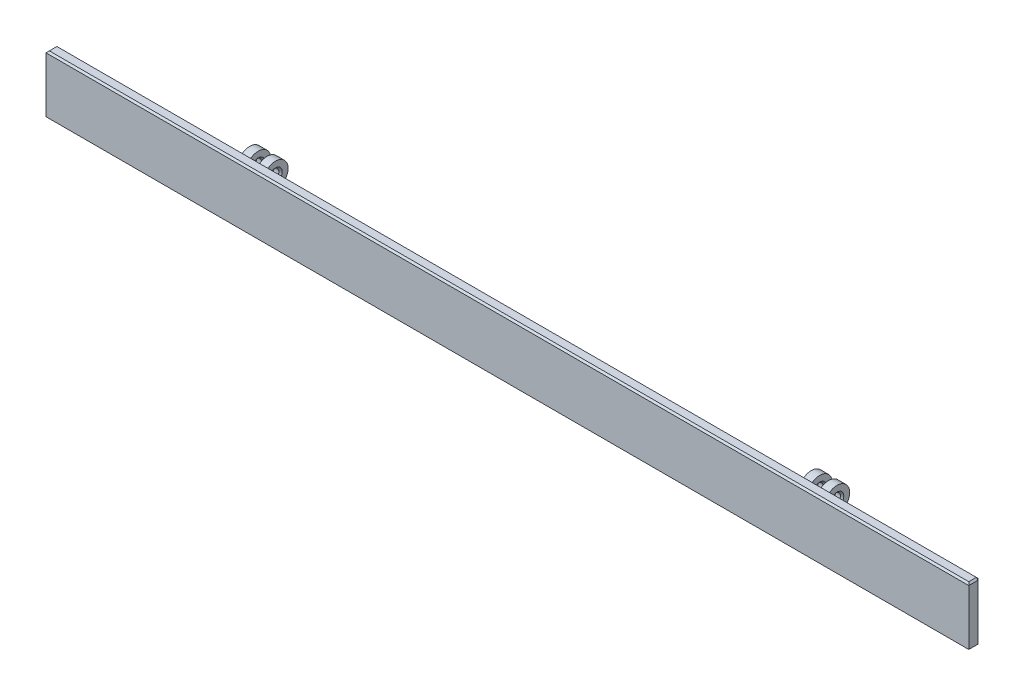
SolidWorks part; units mm, degrees
ref_plane "前视基准面" through (0, 0, 0) normal (0, 0, 1) x (1, 0, 0)
ref_plane "上视基准面" through (0, 0, 0) normal (0, 1, 0) x (1, 0, 0)
ref_plane "右视基准面" through (0, 0, 0) normal (1, 0, 0) x (0, 0, -1)
other "Configuration Table"
sketch "草图1" plane through (0, 0, 0) normal (1, 0, 0) x (0, 0, -1)
  line L1 (0, 0) -> (6.5, 0)
  line L2 (0, 0) -> (0, -35)
  line L3 (0, -35) -> (6.5, -35)
  line L4 (6.5, 0) -> (6.5, -35)
  dimension "D1" = 35
  dimension "D2" = 6.5
extrude "凸台-拉伸1" add sketch "草图1" along normal blind 550
ref_plane "基准面1" through (450, 0, 0) normal (1, 0, 0) x (0, 0, -1)
sketch "草图3" plane through (450, 0, 0) normal (1, 0, 0) x (0, 0, -1)
  line L0 (6.5, -17.5) -> (31.5071, -17.5) construction
  line L1 (6.5, -35) -> (6.5, 0) construction
  line L3 (6.5, -17.5) -> (18.5, -17.5) construction
  line L4 (6.5, -21.25) -> (6.5, -13.75)
  line L7 (6.5, -13.75) -> (15.0048, -13.75)
  line L8 (6.5, -21.25) -> (15.0048, -21.25)
  circle A0 centre (21.5, -17.5) radius 3
  arc A1 (15.0048, -21.25) -> (15.0048, -13.75) centre (21.5, -17.5) ccw
  circle A2 centre (21.5, -17.5) radius 7.5 construction
  dimension "D3" = 6
  dimension "D4" = 15
  dimension "D1" = 4.5
  dimension "D2" = 7.5
extrude "凸台-拉伸2" add sketch "草图3" against normal blind 5
ref_plane "基准面2" through (442.35, 0, 0) normal (-1, 0, 0) x (0, 0, 1)
mirror "镜向1" about plane through (442.35, 0, 0) normal (-1, 0, 0) of "凸台-拉伸2"
ref_plane "基准面3" through (275, 0, 0) normal (1, 0, 0) x (0, 0, -1)
mirror "镜向2" about plane through (275, 0, 0) normal (1, 0, 0) of "镜向1", "凸台-拉伸2"
chamfer "倒角1" distance 1 angle 45 30 edges at (112.8, -13.75, -6.5) (115.3, -17.5, -6.5) (112.8, -21.25, -6.5) (110.3, -17.5, -6.5) (439.7, -17.5, -6.5) (437.2, -21.25, -6.5) (434.7, -17.5, -6.5) (437.2, -13.75, -6.5) (447.5, -13.75, -6.5) (450, -17.5, -6.5) (447.5, -21.25, -6.5) (445, -17.5, -6.5) (105, -17.5, -6.5) (102.5, -21.25, -6.5) (100, -17.5, -6.5) (102.5, -13.75, -6.5) (550, -17.5, -6.5) (275, -35, 0) (550, -35, -3.25) (275, -35, -6.5) (0, -35, -3.25) (0, -17.5, -6.5) (275, 0, -6.5) (550, 0, -3.25) (275, 0, 0) (0, 0, -3.25) (450, -17.5, -24.5) (445, -17.5, -24.5) (434.7, -17.5, -24.5) (439.7, -17.5, -24.5)
chamfer "倒角2" distance 1 angle 45 4 edges at (110.3, -17.5, -24.5) (100, -17.5, -24.5) (105, -17.5, -24.5) (115.3, -17.5, -24.5)
